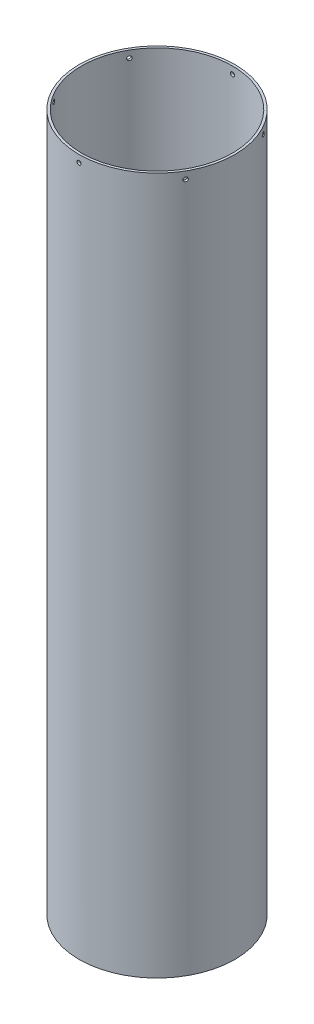
SolidWorks part; units mm, degrees
ref_plane "Front Plane" through (0, 0, 0) normal (0, 0, 1) x (1, 0, 0)
ref_plane "Top Plane" through (0, 0, 0) normal (0, 1, 0) x (1, 0, 0)
ref_plane "Right Plane" through (0, 0, 0) normal (1, 0, 0) x (0, 0, -1)
sketch "Sketch1" plane through (0, 0, 0) normal (0, 1, 0) x (1, 0, 0)
  circle A0 centre (0, 0) radius 51.1048
  circle A1 centre (0, 0) radius 49.53
  dimension "D1" = 102.2096
  dimension "D2" = 99.06
extrude "Boss-Extrude1" add sketch "Sketch1" along normal blind 457.2
sketch "Sketch2" plane through (0, 0, 0) normal (0, 0, 1) x (1, 0, 0)
  line L0 (0, 457.2) -> (0, 452.4375)
  line L1 (49.53, 457.2) -> (-49.53, 457.2) construction
  circle A0 centre (0, 452.4375) radius 1.3525
  point P5 (0, 0)
  dimension "D2" = 2.7051
  dimension "D1" = 4.7625
extrude "Cut-Extrude1" cut sketch "Sketch2" against normal through all
ref_axis "Axis1" through (0, 457.2, 0) along (0, -1, 0)
pattern_circular "CirPattern1" count 6 over 360 about axis through (0, 457.2, 0) along (0, -1, 0) of "Cut-Extrude1"
equation "\"Body_Tube_OD\"= 4.024in"
equation "\"Body_Tube_ID\"= 3.90in"
equation "\"D1@Sketch1\"=\"Body_Tube_OD\""
equation "\"D2@Sketch1\"=\"Body_Tube_ID\""
equation "\"Aft_Lower_Tube_Length\" = 18in"
equation "\"D1@Boss-Extrude1\"=\"Aft_Lower_Tube_Length\""
equation "\"AB_Coupling_Section_Length\"= 0.375in"
equation "\"AB_Coupler_Num_Screws\"= 6"
equation "\"AB_Coupling_Screw_Diameter\"= 0.1065in"
equation "\"D2@Sketch2\"=\"AB_Coupling_Screw_Diameter\""
equation "\"D1@CirPattern1\"=\"AB_Coupler_Num_Screws\""
equation "\"D1@Sketch2\"=\"AB_Coupling_Section_Length\"/2"
